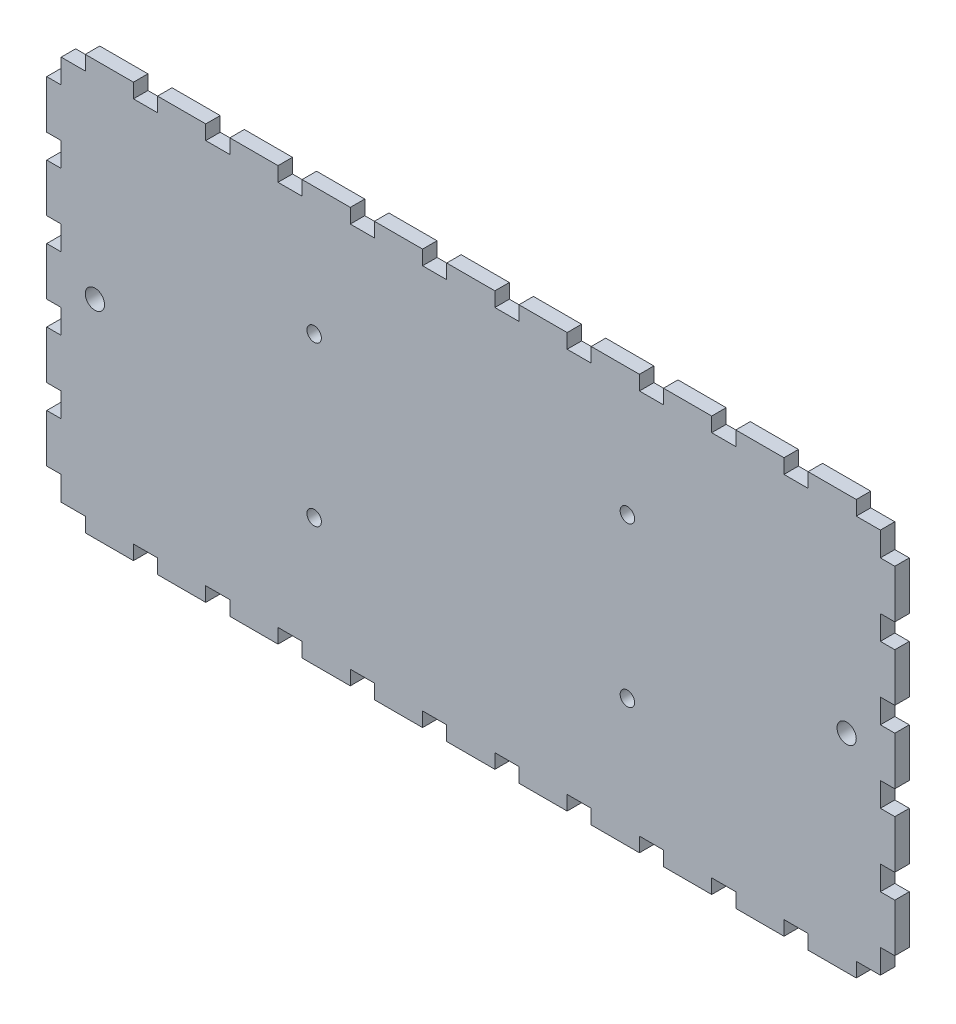
SolidWorks part; units mm, degrees
material "轻木"
ref_plane "前视基准面" through (0, 0, 0) normal (0, 0, 1) x (1, 0, 0)
ref_plane "上视基准面" through (0, 0, 0) normal (0, 1, 0) x (1, 0, 0)
ref_plane "右视基准面" through (0, 0, 0) normal (1, 0, 0) x (0, 0, -1)
sketch "草图2" plane through (0, 0, 0) normal (0, 0, 1) x (1, 0, 0)
  line L1 (-85, 40) -> (-80, 40)
  line L2 (-85, 40) -> (-85, 35)
  line L3 (-85, -40) -> (-80, -40)
  line L4 (85, 40) -> (85, 35)
  line L5 (-85, 40) -> (85, -40) construction
  line L6 (-85, -40) -> (85, 40) construction
  line L7 (-85, 35) -> (-88, 35)
  line L9 (-85, 25) -> (-88, 25)
  line L10 (-88, 35) -> (-88, 25)
  line L11 (-85, 20) -> (-88, 20)
  line L12 (-88, 20) -> (-88, 10)
  line L13 (-85, 10) -> (-88, 10)
  line L15 (-85, 5) -> (-88, 5)
  line L16 (-88, 5) -> (-88, -5)
  line L17 (-85, -5) -> (-88, -5)
  line L19 (-85, -10) -> (-88, -10)
  line L20 (-88, -10) -> (-88, -20)
  line L21 (-85, -20) -> (-88, -20)
  line L23 (-85, -25) -> (-88, -25)
  line L24 (-88, -25) -> (-88, -35)
  line L25 (-85, -35) -> (-88, -35)
  line L26 (0, -55) -> (0, 55) construction
  line L27 (85, -25) -> (88, -25)
  line L28 (88, -25) -> (88, -35)
  line L29 (85, -35) -> (88, -35)
  line L31 (85, -10) -> (88, -10)
  line L32 (88, -10) -> (88, -20)
  line L33 (85, -20) -> (88, -20)
  line L35 (85, 5) -> (88, 5)
  line L36 (88, 5) -> (88, -5)
  line L37 (85, -5) -> (88, -5)
  line L39 (85, 20) -> (88, 20)
  line L40 (88, 20) -> (88, 10)
  line L41 (85, 10) -> (88, 10)
  line L43 (85, 25) -> (88, 25)
  line L44 (85, 35) -> (88, 35)
  line L45 (88, 35) -> (88, 25)
  line L46 (-65, 40) -> (-65, 43)
  line L48 (-80, 40) -> (-80, 43)
  line L49 (-80, 43) -> (-70, 43)
  line L50 (-70, 40) -> (-70, 43)
  line L52 (-55, 40) -> (-55, 43)
  line L53 (-65, 43) -> (-55, 43)
  line L54 (-50, 40) -> (-50, 43)
  line L56 (-40, 40) -> (-40, 43)
  line L57 (-50, 43) -> (-40, 43)
  line L58 (-35, 40) -> (-35, 43)
  line L60 (-25, 40) -> (-25, 43)
  line L61 (-35, 43) -> (-25, 43)
  line L62 (-20, 40) -> (-20, 43)
  line L64 (-10, 40) -> (-10, 43)
  line L65 (-20, 43) -> (-10, 43)
  line L66 (-5, 40) -> (-5, 43)
  line L68 (5, 40) -> (5, 43)
  line L69 (-5, 43) -> (5, 43)
  line L70 (10, 40) -> (10, 43)
  line L72 (20, 40) -> (20, 43)
  line L73 (10, 43) -> (20, 43)
  line L74 (25, 40) -> (25, 43)
  line L76 (35, 40) -> (35, 43)
  line L77 (25, 43) -> (35, 43)
  line L78 (40, 40) -> (40, 43)
  line L80 (50, 40) -> (50, 43)
  line L81 (40, 43) -> (50, 43)
  line L82 (55, 40) -> (55, 43)
  line L84 (65, 40) -> (65, 43)
  line L85 (55, 43) -> (65, 43)
  line L86 (70, 40) -> (70, 43)
  line L88 (80, 40) -> (80, 43)
  line L89 (70, 43) -> (80, 43)
  line L90 (55, 0) -> (-55, 0) construction
  line L92 (80, -40) -> (80, -43)
  line L93 (70, -43) -> (80, -43)
  line L94 (70, -40) -> (70, -43)
  line L96 (65, -40) -> (65, -43)
  line L97 (55, -43) -> (65, -43)
  line L98 (55, -40) -> (55, -43)
  line L100 (50, -40) -> (50, -43)
  line L101 (40, -43) -> (50, -43)
  line L102 (40, -40) -> (40, -43)
  line L104 (35, -40) -> (35, -43)
  line L105 (25, -43) -> (35, -43)
  line L106 (25, -40) -> (25, -43)
  line L108 (20, -40) -> (20, -43)
  line L109 (10, -43) -> (20, -43)
  line L110 (10, -40) -> (10, -43)
  line L112 (5, -40) -> (5, -43)
  line L113 (-5, -43) -> (5, -43)
  line L114 (-5, -40) -> (-5, -43)
  line L116 (-10, -40) -> (-10, -43)
  line L117 (-20, -43) -> (-10, -43)
  line L118 (-20, -40) -> (-20, -43)
  line L120 (-25, -40) -> (-25, -43)
  line L121 (-35, -43) -> (-25, -43)
  line L122 (-35, -40) -> (-35, -43)
  line L124 (-40, -40) -> (-40, -43)
  line L125 (-50, -43) -> (-40, -43)
  line L126 (-50, -40) -> (-50, -43)
  line L128 (-55, -40) -> (-55, -43)
  line L129 (-65, -43) -> (-55, -43)
  line L130 (-65, -40) -> (-65, -43)
  line L131 (-80, -43) -> (-70, -43)
  line L132 (-70, -40) -> (-70, -43)
  line L134 (-80, -40) -> (-80, -43)
  line L135 (-85, 25) -> (-85, 20)
  line L136 (-85, 10) -> (-85, 5)
  line L137 (-85, -5) -> (-85, -10)
  line L138 (-85, -20) -> (-85, -25)
  line L139 (-85, -35) -> (-85, -40)
  line L140 (-70, 40) -> (-65, 40)
  line L141 (-55, 40) -> (-50, 40)
  line L142 (-40, 40) -> (-35, 40)
  line L143 (-10, 40) -> (-5, 40)
  line L144 (5, 40) -> (10, 40)
  line L145 (20, 40) -> (25, 40)
  line L146 (35, 40) -> (40, 40)
  line L147 (50, 40) -> (55, 40)
  line L148 (65, 40) -> (70, 40)
  line L149 (80, 40) -> (85, 40)
  line L150 (-25, 40) -> (-20, 40)
  line L151 (85, 10) -> (85, 5)
  line L152 (85, -5) -> (85, -10)
  line L153 (85, -20) -> (85, -25)
  line L154 (85, -35) -> (85, -40)
  line L155 (80, -40) -> (85, -40)
  line L156 (65, -40) -> (70, -40)
  line L157 (-70, -40) -> (-65, -40)
  line L158 (-55, -40) -> (-50, -40)
  line L159 (-40, -40) -> (-35, -40)
  line L160 (-25, -40) -> (-20, -40)
  line L161 (-10, -40) -> (-5, -40)
  line L162 (5, -40) -> (10, -40)
  line L163 (20, -40) -> (25, -40)
  line L164 (35, -40) -> (40, -40)
  line L165 (50, -40) -> (55, -40)
  line L166 (85, 25) -> (85, 20)
  point P0 (0, 0)
  dimension "D1" = 170
  dimension "D2" = 80
  dimension "D3" = 3
  dimension "D4" = 10
  dimension "D5" = 5
  dimension "D7" = 3
  dimension "D8" = 10
  dimension "D9" = 5
  dimension "D6" = 5
  dimension "D10" = 11
extrude "凸台-拉伸1" add sketch "草图2" along normal blind 3
sketch "草图3" plane through (0, 0, 3) normal (0, 0, 1) x (1, 0, 0)
  line L1 (-32.5, 16.5) -> (32.5, 16.5) construction
  line L2 (-32.5, 16.5) -> (-32.5, -16.5) construction
  line L3 (-32.5, -16.5) -> (32.5, -16.5) construction
  line L4 (32.5, 16.5) -> (32.5, -16.5) construction
  line L5 (-32.5, 16.5) -> (32.5, -16.5) construction
  line L6 (-32.5, -16.5) -> (32.5, 16.5) construction
  circle A0 centre (-32.5, 16.5) radius 1.5
  circle A1 centre (32.5, 16.5) radius 1.5
  circle A2 centre (32.5, -16.5) radius 1.5
  circle A3 centre (-32.5, -16.5) radius 1.5
  point P0 (0, 0)
  dimension "D1" = 65
  dimension "D2" = 33
extrude "切除-拉伸2" cut sketch "草图3" against normal blind 3
sketch "草图4" plane through (0, 0, 3) normal (0, 0, 1) x (1, 0, 0)
  line L1 (-78, 32.5) -> (78, 32.5) construction
  line L2 (-78, 32.5) -> (-78, -32.5) construction
  line L3 (-78, -32.5) -> (78, -32.5) construction
  line L4 (78, 32.5) -> (78, -32.5) construction
  line L5 (-78, 32.5) -> (78, -32.5) construction
  line L6 (-78, -32.5) -> (78, 32.5) construction
  circle A4 centre (78, 0) radius 2
  circle A5 centre (-78, 0) radius 2
  point P0 (0, 0)
  dimension "D1" = 156
  dimension "D2" = 65
extrude "切除-拉伸3" cut sketch "草图4" against normal blind 3
